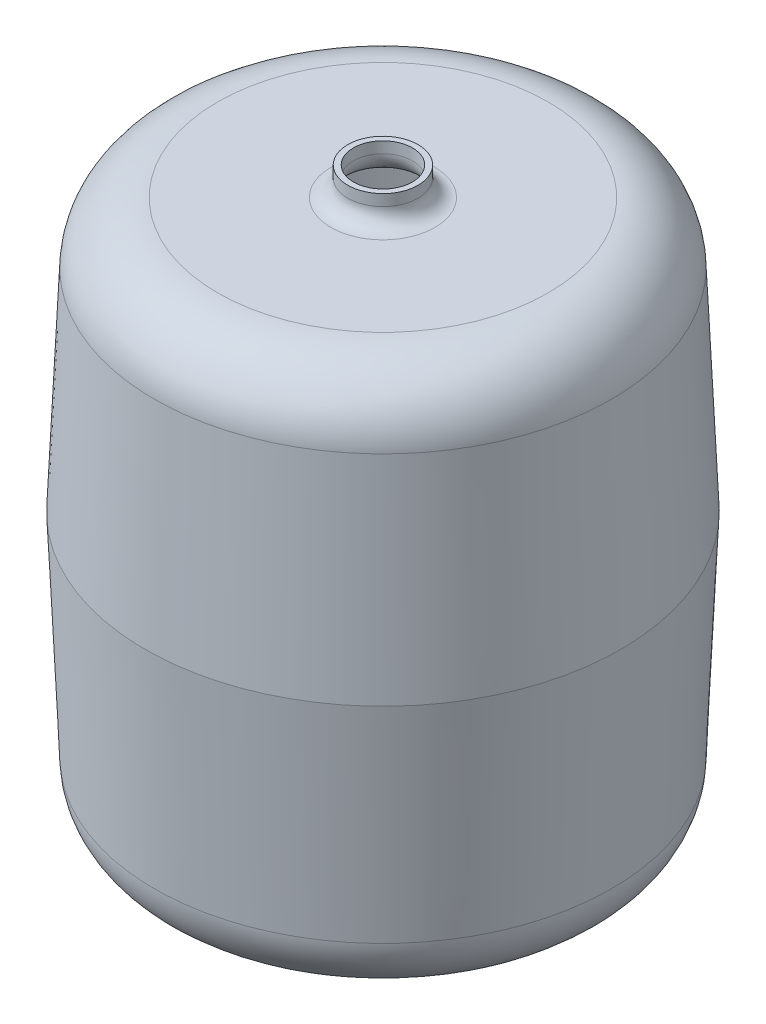
SolidWorks part; units mm, degrees
material "1060 Alloy"
ref_plane "Front Plane" through (0, 0, 0) normal (0, 0, 1) x (1, 0, 0)
ref_plane "Top Plane" through (0, 0, 0) normal (0, 1, 0) x (1, 0, 0)
ref_plane "Right Plane" through (0, 0, 0) normal (1, 0, 0) x (0, 0, -1)
sketch "Sketch1" plane through (0, 0, 0) normal (0, 0, 1) x (1, 0, 0)
  line L0 (0, 0) -> (50000, 0) construction
  line L1 (0, 0) -> (0, 50000) construction
  line L2 (0, -193.75) -> (-117.5428, -193.75)
  line L3 (-162.5, -150.7129) -> (-169.0803, 0)
  line L4 (-37, 193.75) -> (-117.5428, 193.75)
  line L5 (-162.5, 150.7129) -> (-169.0803, 0)
  line L6 (-25, 205.75) -> (-25, 213.75)
  line L7 (-21, 205.75) -> (-21, 213.75)
  line L8 (-37, 189.75) -> (-117.5428, 189.75)
  line L9 (-158.5038, 150.5384) -> (-165.0765, 0)
  line L10 (-158.5038, -150.5384) -> (-165.0765, 0)
  line L11 (0, -189.75) -> (-117.5428, -189.75)
  line L12 (-25, 213.75) -> (-21, 213.75)
  line L13 (0, -193.75) -> (0, -189.75)
  arc A0 (-162.5, -150.7129) -> (-117.5428, -193.75) centre (-117.5428, -148.75) ccw
  arc A1 (-162.5, 150.7129) -> (-117.5428, 193.75) centre (-117.5428, 148.75) cw
  arc A2 (-37, 193.75) -> (-25, 205.75) centre (-37, 205.75) ccw
  arc A3 (-37, 189.75) -> (-21, 205.75) centre (-37, 205.75) ccw
  arc A4 (-158.5038, 150.5384) -> (-117.5428, 189.75) centre (-117.5428, 148.75) cw
  arc A5 (-158.5038, -150.5384) -> (-117.5428, -189.75) centre (-117.5428, -148.75) ccw
  dimension "D4" = 90
  dimension "D7" = 12
  dimension "D1" = 92.5
  dimension "D2" = 325
  dimension "D3" = 387.5
  dimension "D5" = 50
  dimension "D6" = 20
  dimension "D8" = 4
revolve "Revolve1" add sketch "Sketch1" angle 360 about L1
equation "\"A\"= 325.00mm"
equation "\"B\"= 387.50mm"
